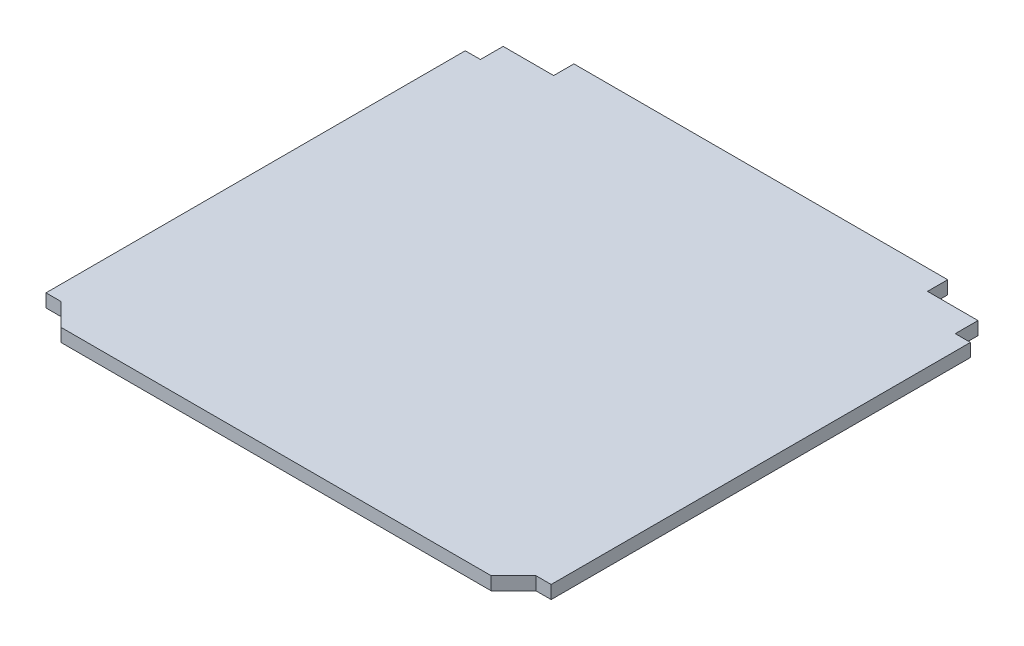
SolidWorks part; units mm, degrees
ref_plane "Front Plane" through (0, 0, 0) normal (0, 0, 1) x (1, 0, 0)
ref_plane "Top Plane" through (0, 0, 0) normal (0, 1, 0) x (1, 0, 0)
ref_plane "Right Plane" through (0, 0, 0) normal (1, 0, 0) x (0, 0, -1)
sketch "Sketch2" plane through (0, 0, 0) normal (0, 1, 0) x (1, 0, 0)
  line L0 (37, 50) -> (-37, 50) construction
  line L1 (50, 50) -> (-50, 50)
  line L2 (50, 50) -> (50, -50)
  line L3 (50, -50) -> (-50, -50)
  line L4 (-50, 50) -> (-50, -50)
  line L5 (-50, -41.5) -> (-50, 41.5) construction
  line L6 (50, 41.5) -> (50, -41.5) construction
  line L7 (37, 50) -> (37, 46)
  line L8 (37, 46) -> (46, 46)
  line L9 (46, 46) -> (47, 46)
  line L10 (47, 46) -> (47, 41.5)
  line L11 (47, 41.5) -> (50.0658, 41.5)
  line L13 (0, 70.3951) -> (0, -61.0345) construction
  line L15 (-84.1689, 0) -> (95.4998, 0) construction
  line L16 (-37, 50) -> (-37, 46)
  line L17 (-37, 46) -> (-46, 46)
  line L18 (-46, 46) -> (-47, 46)
  line L19 (-47, 46) -> (-47, 41.5)
  line L20 (-47, 41.5) -> (-50.0658, 41.5)
  line L21 (18.75, -50) -> (13.25, -50) construction
  line L22 (-37, -50) -> (-37, -47)
  line L23 (-37, -47) -> (-41.5, -47)
  line L24 (-41.5, -47) -> (-47, -41.5)
  line L25 (-47, -41.5) -> (-50, -41.5)
  line L26 (37, -50) -> (37, -47)
  line L27 (37, -47) -> (41.5, -47)
  line L28 (41.5, -47) -> (47, -41.5)
  line L29 (47, -41.5) -> (50, -41.5)
  line L30 (-50, -45.9311) -> (50, -45.9311)
extrude "Boss-Extrude1" add sketch "Sketch2" along normal up to surface (2.6 mm away) contours L11 L10 L9 L8 L7 L1 L4 L3 L2
